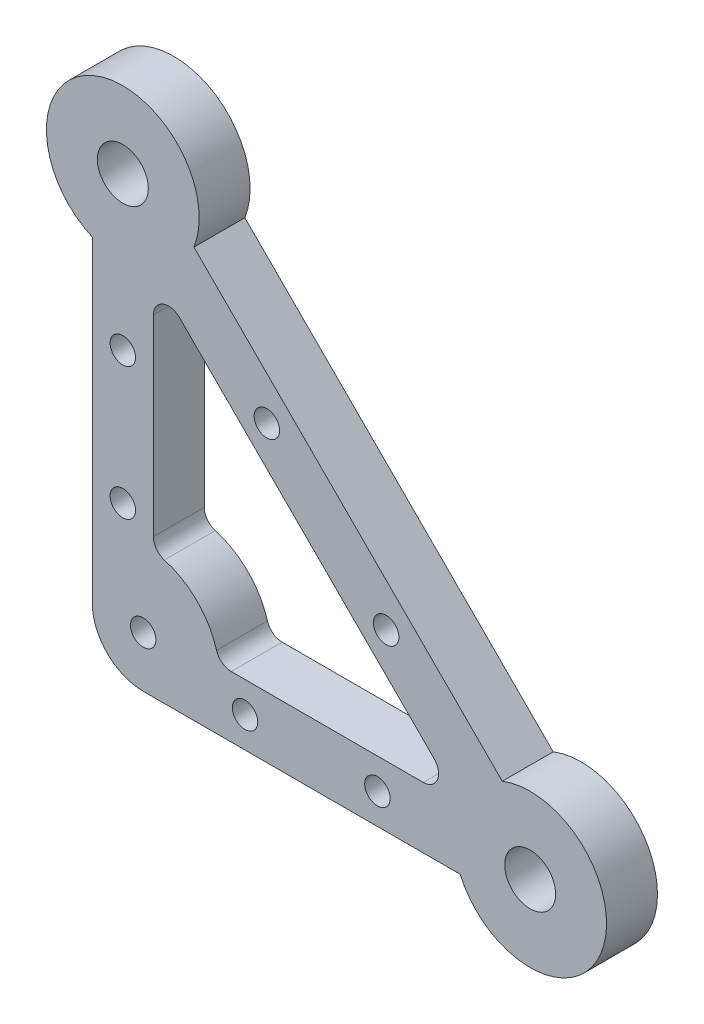
SolidWorks part; units mm, degrees
ref_plane "Plano frontal" through (0, 0, 0) normal (0, 0, 1) x (1, 0, 0)
ref_plane "Plano superior" through (0, 0, 0) normal (0, 1, 0) x (1, 0, 0)
ref_plane "Plano direito" through (0, 0, 0) normal (1, 0, 0) x (0, 0, -1)
sketch "Esboço1" plane through (0, 0, 0) normal (0, 0, 1) x (1, 0, 0)
  line L0 (-6, -76) -> (-6, -13.7477)
  line L1 (4, -86) -> (66.2523, -86)
  line L2 (0, 0) -> (80, -80) construction
  line L3 (21.2916, -74) -> (59.0096, -74)
  line L4 (13.9638, -5.4785) -> (74.5215, -66.0362)
  line L5 (11.1213, -18.869) -> (61.131, -68.8787)
  line L6 (6, -20.9904) -> (6, -58.7084)
  arc A0 (13.9638, -5.4785) -> (-6, -13.7477) centre (0, 0) ccw
  circle A2 centre (0, 0) radius 5
  circle A3 centre (0, -30) radius 2.5
  circle A4 centre (0, -56) radius 2.5
  circle A5 centre (4, -76) radius 2.5
  circle A6 centre (24, -80) radius 2.5
  circle A7 centre (50, -80) radius 2.5
  circle A8 centre (80, -80) radius 5
  arc A9 (66.2523, -86) -> (74.5215, -66.0362) centre (80, -80) ccw
  circle A10 centre (28.2843, -28.2843) radius 2.5
  circle A11 centre (51.7157, -51.7157) radius 2.5
  arc A12 (-6, -76) -> (4, -86) centre (4, -76) ccw
  arc A13 (18.4097, -71.8333) -> (8.1667, -61.5903) centre (4, -76) ccw
  arc A14 (11.1213, -18.869) -> (6, -20.9904) centre (9, -20.9904) ccw
  arc A15 (59.0096, -74) -> (61.131, -68.8787) centre (59.0096, -71) ccw
  arc A16 (21.2916, -74) -> (18.4097, -71.8333) centre (21.2916, -71) cw
  arc A17 (6, -58.7084) -> (8.1667, -61.5903) centre (9, -58.7084) ccw
  point P13 (6, -13.7477)
  point P34 (6, -39.8494)
  dimension "D1" = 30
  dimension "D2" = 10
  dimension "D3" = 5
  dimension "D7" = 20
  dimension "D8" = 4
  dimension "D11" = 10
  dimension "D13" = 30
  dimension "D14" = 40
  dimension "D16" = 20
  dimension "D17" = 30
  dimension "D22" = 3
  dimension "D23" = 3
  dimension "D24" = 3
  dimension "D25" = 3
  dimension "D4" = 30
  dimension "D5" = 26
  dimension "D6" = 4
  dimension "D9" = 20
  dimension "D10" = 26
  dimension "D12" = 30
  dimension "D15" = 40
  dimension "D18" = 6
  dimension "D19" = 6
  dimension "D20" = 6
  dimension "D21" = 12
extrude "Ressalto-extrusão1" add sketch "Esboço1" along normal blind 10
